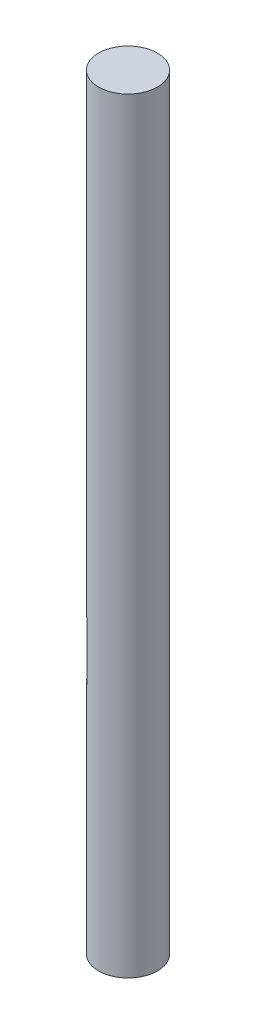
SolidWorks part; units mm, degrees
ref_plane "Front Plane" through (0, 0, 0) normal (0, 0, 1) x (1, 0, 0)
ref_plane "Top Plane" through (0, 0, 0) normal (0, 1, 0) x (1, 0, 0)
ref_plane "Right Plane" through (0, 0, 0) normal (1, 0, 0) x (0, 0, -1)
sketch "Sketch1" plane through (0, 0, 0) normal (0, 1, 0) x (1, 0, 0)
  circle A0 centre (0, 0) radius 3.175
  dimension "D1" = 6.35
extrude "Boss-Extrude1" add sketch "Sketch1" along normal mid plane 57.15
sketch "Sketch2" plane through (0, 28.575, 0) normal (0, 1, 0) x (1, 0, 0)
  line L0 (-1.905, 2.54) -> (-1.905, -2.54)
  circle A0 centre (0, 0) radius 3.175 construction
  arc A1 (-1.905, 2.54) -> (-1.905, -2.54) centre (0, 0) ccw
  dimension "D1" = 1.905
extrude "Cut-Extrude1" cut sketch "Sketch2" against normal mid plane 6.35 from surface at -28.575 starting at plane "Top Plane"
sketch "Sketch3" plane through (0, 28.575, 0) normal (0, 1, 0) x (1, 0, 0)
  circle A0 centre (0, 0) radius 3.175
extrude "Boss-Extrude2" add sketch "Sketch3" along normal blind 25.4
